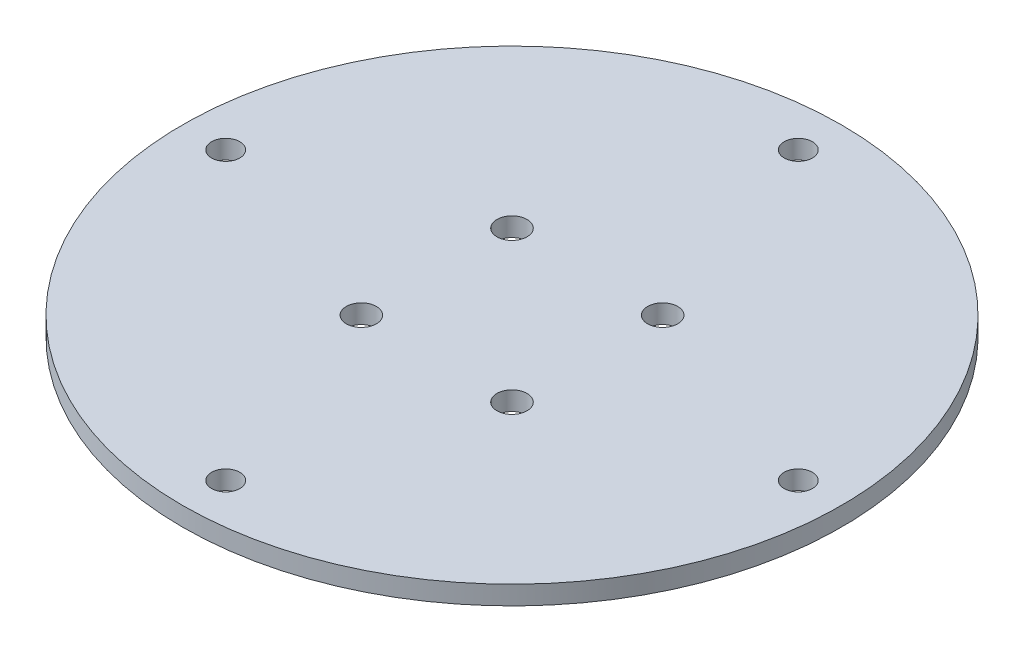
SolidWorks part; units mm, degrees
ref_plane "Front Plane" through (0, 0, 0) normal (0, 0, 1) x (1, 0, 0)
ref_plane "Top Plane" through (0, 0, 0) normal (0, 1, 0) x (1, 0, 0)
ref_plane "Right Plane" through (0, 0, 0) normal (1, 0, 0) x (0, 0, -1)
sketch "Sketch1" plane through (0, 0, 0) normal (0, 1, 0) x (1, 0, 0)
  line L1 (30.4056, 0) -> (0, 30.4056) construction
  line L2 (0, 30.4056) -> (-30.4056, 0) construction
  line L3 (-30.4056, 0) -> (0, -30.4056) construction
  line L4 (0, -30.4056) -> (30.4056, 0) construction
  line L5 (-8, 8) -> (8, 8) construction
  line L6 (-8, 8) -> (-8, -8) construction
  line L7 (-8, -8) -> (8, -8) construction
  line L8 (8, 8) -> (8, -8) construction
  line L9 (-8, 8) -> (8, -8) construction
  line L10 (-8, -8) -> (8, 8) construction
  circle A1 centre (0, 0) radius 21.5 construction
  circle A2 centre (0, 30.4056) radius 1.5
  circle A3 centre (30.4056, 0) radius 1.5
  circle A4 centre (0, -30.4056) radius 1.5
  circle A5 centre (-30.4056, 0) radius 1.5
  circle A7 centre (0, 0) radius 35
  circle A8 centre (-8, 8) radius 1.6
  circle A9 centre (8, 8) radius 1.6
  circle A10 centre (8, -8) radius 1.6
  circle A11 centre (-8, -8) radius 1.6
  point P18 (0, 0)
  point P32 (0, 0)
  dimension "D2" = 3
  dimension "D5" = 70
  dimension "D7" = 3.2
  dimension "D1" = 43
  dimension "D6" = 16
  dimension "D3" = 4
  dimension "D8" = 4
extrude "Boss-Extrude1" add sketch "Sketch1" along normal blind 2
